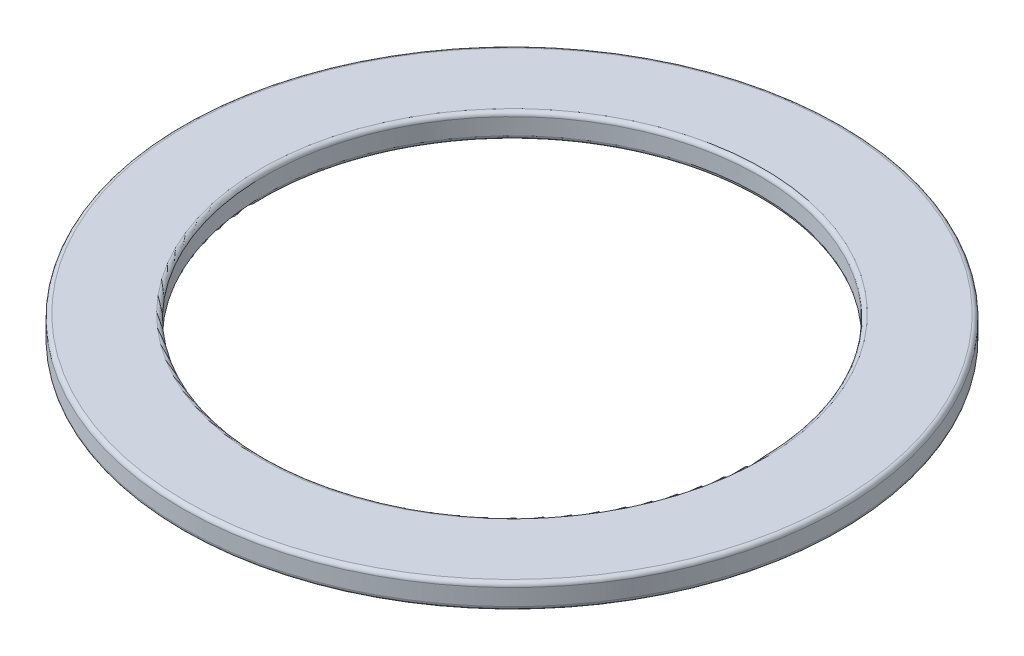
SolidWorks part; units mm, degrees
ref_plane "前视基准面" through (0, 0, 0) normal (0, 0, 1) x (1, 0, 0)
ref_plane "上视基准面" through (0, 0, 0) normal (0, 1, 0) x (1, 0, 0)
ref_plane "右视基准面" through (0, 0, 0) normal (1, 0, 0) x (0, 0, -1)
other "Configuration Table"
sketch "草图1" plane through (0, 0, 0) normal (0, 1, 0) x (1, 0, 0)
  circle A0 centre (0, 0) radius 3
  circle A1 centre (0, 0) radius 4
  dimension "D1" = 6
  dimension "D2" = 8
extrude "凸台-拉伸1" add sketch "草图1" along normal blind 0.3
fillet "圆角2" radius 0.05 4 edges at (0, 0, 3) (0, 0.3, 3) (0, 0, 4) (0, 0.3, 4)
